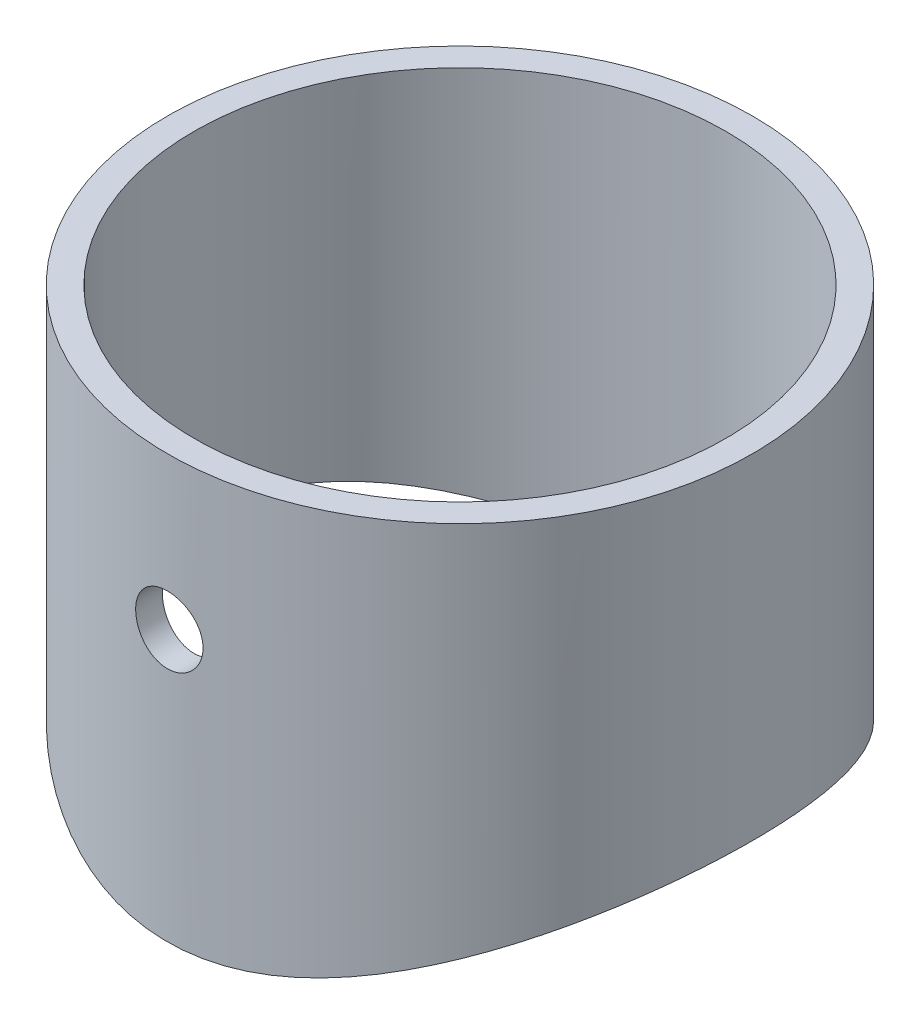
SolidWorks part; units mm, degrees
material " 12Х18Н10Т ГОСТ 4543-71"
ref_plane "Спереди" through (0, 0, 0) normal (0, 0, 1) x (1, 0, 0)
ref_plane "Сверху" through (0, 0, 0) normal (0, 1, 0) x (1, 0, 0)
ref_plane "Справа" through (0, 0, 0) normal (1, 0, 0) x (0, 0, -1)
sketch "Эскиз1" plane through (0, 0, 0) normal (0, 0, 1) x (1, 0, 0)
  line L0 (0, 0) -> (0, 62.274) construction
  line L1 (-150, 0) -> (-150, 239)
  line L2 (-165, 0) -> (-165, 239)
  line L3 (-165, 239) -> (-150, 239)
  line L4 (-150, 0) -> (-165, 0)
  dimension "D1" = 300
  dimension "D2" = 239
  dimension "D3" = 15
revolve "Повернуть1" add sketch "Эскиз1" angle 360 about L0
sketch "Sketch1" plane through (2479, 0, 0) normal (1, 0, 0) x (0, 0, -1)
  circle A0 centre (0, -250) radius 300
extrude "Cut-Extrude1" cut sketch "Sketch1" against normal through all
sketch "Sketch2" plane through (0, 0, 0) normal (0, 0, 1) x (1, 0, 0)
  line L0 (0, 293) -> (0, 153) construction
  circle A0 centre (0, 153) radius 19
  dimension "D1" = 38
extrude "Cut-Extrude2" cut sketch "Sketch2" along normal through all
